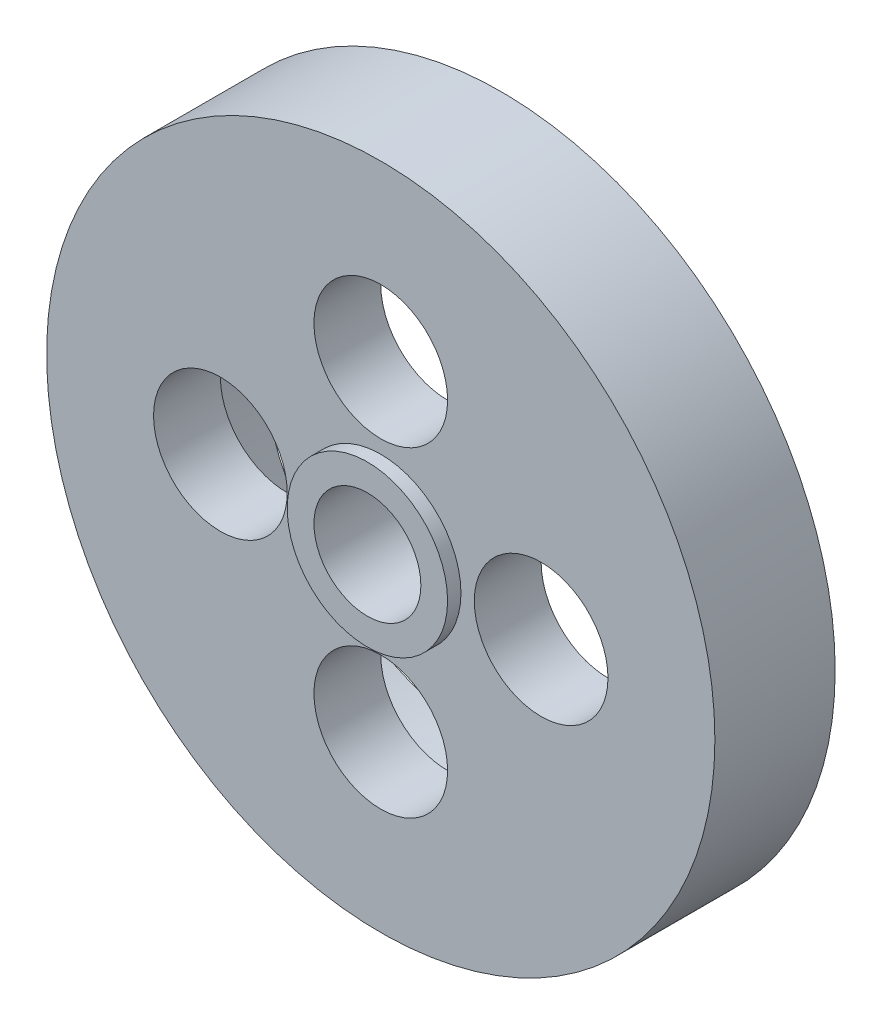
SolidWorks part; units mm, degrees
ref_plane "Front Plane" through (0, 0, 0) normal (0, 0, 1) x (1, 0, 0)
ref_plane "Top Plane" through (0, 0, 0) normal (0, 1, 0) x (1, 0, 0)
ref_plane "Right Plane" through (0, 0, 0) normal (1, 0, 0) x (0, 0, -1)
sketch "Sketch1" plane through (0, 0, 0) normal (0, 0, 1) x (1, 0, 0)
  circle A0 centre (0, 0) radius 25
  circle A1 centre (0, 0) radius 12 construction
  circle A2 centre (0, 12) radius 5
  circle A3 centre (12, 0) radius 5
  circle A4 centre (0, -12) radius 5
  circle A5 centre (-12, 0) radius 5
  circle A6 centre (0, 0) radius 4
  point P15 (0, 0)
  dimension "D1" = 50
  dimension "D2" = 24
  dimension "D3" = 4
  dimension "10" = 10
  dimension "D4" = 8
extrude "Boss-Extrude1" add sketch "Sketch1" along normal blind 9
sketch "Sketch2" plane through (0, 0, 0) normal (0, 0, -1) x (-1, 0, 0)
  circle A0 centre (0, 0) radius 18
  dimension "D1" = 36
extrude "Cut-Extrude1" cut sketch "Sketch2" against normal blind 4
sketch "Sketch3" plane through (0, 0, 9) normal (0, 0, 1) x (1, 0, 0)
  circle A0 centre (0, 0) radius 6
  circle A1 centre (0, 0) radius 4 construction
  circle A2 centre (0, 0) radius 4
  dimension "D1" = 12
extrude "Boss-Extrude2" add sketch "Sketch3" along normal blind 1
